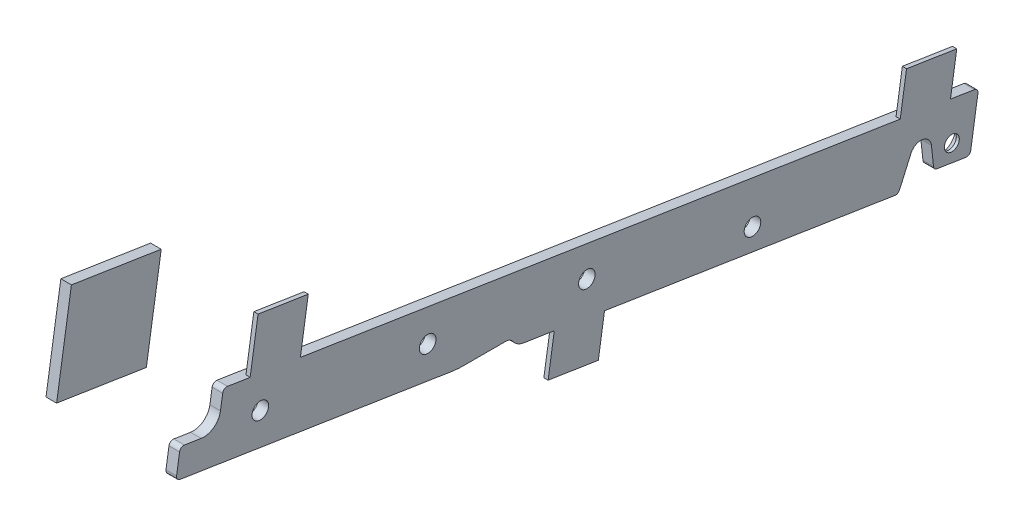
SolidWorks part; units mm, degrees
material "6061-T6 (SS)"
ref_plane "Front Plane" through (0, 0, 0) normal (0, 0, 1) x (1, 0, 0)
ref_plane "Top Plane" through (0, 0, 0) normal (0, 1, 0) x (1, 0, 0)
ref_plane "Right Plane" through (0, 0, 0) normal (1, 0, 0) x (0, 0, -1)
sketch "Sketch1" plane through (0, 0, 0) normal (1, 0, 0) x (0, 0, -1)
  line L0 (0, 0) -> (-69.3361, 0) construction
  line L1 (0, 0) -> (0, 19.05) construction
  line L2 (0, 19.05) -> (-75.5537, 19.05) construction
  line L3 (-60.6679, 12.573) -> (-60.6679, 19.05) construction
  line L4 (-60.6679, 12.573) -> (-61.6659, 6.1734) construction
  line L5 (-60.6679, 12.573) -> (-9.8679, 12.573) construction
  line L6 (-9.8679, 12.573) -> (-9.8679, 9.12) construction
  line L7 (-60.6679, 12.573) -> (-111.4679, 12.573) construction
  line L8 (-111.4679, 12.573) -> (-111.4679, 10.7443) construction
  line L9 (-60.6679, 12.573) -> (-110.8612, 20.4008) construction
  line L10 (-110.8612, 20.4008) -> (-110.3291, 23.8125) construction
  line L11 (-60.6679, 12.573) -> (-10.4746, 4.7452) construction
  line L12 (-10.4746, 4.7452) -> (-10.1928, 6.5521) construction
  line L13 (-233.578, 32.9834) -> (-149.1199, 19.812)
  line L14 (-13.1312, 7.852) -> (-16.9583, -0.7989)
  line L15 (-6.9981, 6.8955) -> (-6.2681, 0.1046)
  line L16 (-6.2681, 0.1046) -> (4.6041, -1.5909)
  line L17 (4.6041, -1.5909) -> (7.1482, 14.7219)
  line L18 (7.1482, 14.7219) -> (-219.3491, 50.0447)
  line L19 (-220.9929, 39.5041) -> (-219.3491, 50.0447)
  line L20 (-220.9929, 39.5041) -> (-232.2864, 41.2653)
  line L21 (-232.2864, 41.2653) -> (-233.578, 32.9834)
  line L22 (-206.8007, 48.0877) -> (-209.7361, 29.2652) construction
  line L23 (-208.2684, 38.6765) -> (-158.0751, 30.8487) construction
  line L24 (-134.62, 17.5507) -> (-134.62, 19.812) construction
  line L25 (-134.62, 19.812) -> (-149.1199, 19.812)
  line L26 (-132.0827, 17.155) -> (-16.9583, -0.7989)
  circle A0 centre (-9.8679, 9.12) radius 4.7879 construction
  circle A1 centre (-111.4679, 10.7443) radius 3.175 construction
  circle A2 centre (-60.6679, 12.573) radius 4.953 construction
  circle A3 centre (-110.3291, 23.8125) radius 2.4892
  circle A4 centre (-110.3291, 23.8125) radius 4.7625 construction
  arc A5 (-6.9981, 6.8955) -> (-13.1312, 7.852) centre (-10.1928, 6.5521) ccw
  circle A6 centre (-60.6679, 12.573) radius 2.4892
  circle A7 centre (-208.2684, 38.6765) radius 5.2942 construction
  circle A8 centre (-158.0751, 30.8487) radius 5.917 construction
  circle A9 centre (-208.2684, 38.6765) radius 2.4892
  circle A10 centre (-158.0751, 30.8487) radius 2.4892
  arc A11 (-134.62, 19.812) -> (-132.0827, 17.155) centre (-134.62, 17.272) cw
  dimension "D1" = 9.5758
  dimension "D2" = 5.08
  dimension "D5" = 6.35
  dimension "D6" = 101.6
  dimension "D8" = 9.906
  dimension "D9" = 1.524
  dimension "D12" = 4.9784
  dimension "D13" = 9.525
  dimension "D14" = 75
  dimension "D15" = 6.4262
  dimension "D20" = 11.43
  dimension "D22" = 12.7
  dimension "D26" = 2.54
  dimension "D3" = 9.12
  dimension "D4" = 19.05
  dimension "D7" = 10.7443
  dimension "D10" = 6.477
  dimension "D11" = 50.8
  dimension "D16" = 2.54
  dimension "D17" = 19.05
  dimension "D18" = 15.875
  dimension "D19" = 111.76
  dimension "D21" = 8.382
  dimension "D23" = 50.8
  dimension "D24" = 134.62
  dimension "D25" = 0.762
extrude "Boss-Extrude1" add sketch "Sketch1" along normal mid plane 3.175
fillet "Fillet1" radius 5.08 1 edges at (0, 39.5041, 220.9929)
fillet "Fillet2" radius 25.4 1 edges at (0, 19.812, 149.1199)
fillet "Fillet3" radius 5.08 1 edges at (0, 17.155, 132.0827)
fillet "Fillet4" radius 1.27 7 edges at (0, 41.2653, 232.2864) (0, 50.0447, 219.3491) (0, 14.7219, -7.1482) (0, -1.5909, -4.6041) (0, 0.1046, 6.2681) (0, -0.7989, 16.9583) (0, 32.9834, 233.578)
hole_wizard "CSK for #8 Oval Head Machine Screw1" positions "Sketch2" profile "Sketch3" countersink size "#8" standard "ANSI Inch" end condition through all
sketch "Sketch2" plane through (-1.5875, 0, 0) normal (-1, 0, 0) x (0, 0, 1)
  line L0 (0.8872, 4.4069) -> (-0.874, 15.7004) construction
  line L1 (-5.8933, 14.9176) -> (218.0942, 49.849) construction
  line L3 (-4.7998, -0.3361) -> (-6.9525, 13.4671) construction
  line L4 (5.3052, -0.0455) -> (-3.3493, -1.3952) construction
  point P0 (0.8872, 4.4069)
  dimension "D1" = 6.35
  dimension "D2" = 5.08
sketch "Sketch3" plane through (-1.5875, 4.4069, 0.8872) normal (0, 1, 0) x (0, 0, 1)
  line L0 (0, 0) -> (0, 3.175)
  line L1 (0, 3.175) -> (2.2479, 3.175)
  line L2 (2.2479, 3.175) -> (2.2479, 2.2645)
  line L3 (2.2479, 2.2645) -> (4.2164, 0)
  line L5 (4.2164, 0) -> (0, 0)
  line L6 (-2.2479, 2.2645) -> (-4.2164, 0) construction
  line L11 (0, -6.35) -> (0, 107.95) construction
  dimension "Thru Hole Dia." = 4.4958
  dimension "Thru Hole Depth" = 3.175
  dimension "Near C'Sink Dia." = 8.4328
  dimension "Near C'Sink Angle" = 82
sketch "Sketch4" plane through (-1.5875, 0, 0) normal (-1, 0, 0) x (0, 0, 1)
  line L35 (24.2002, 1.6659) -> (15.6235, 21.0533)
  line L36 (16.564, 0.0923) -> (13.1312, 7.852) construction
  line L43 (-1.3461, 10.4854) -> (0.2195, 0.4467)
  line L44 (215.1125, 44.2426) -> (-1.3461, 10.4854)
  line L45 (215.1908, 43.7406) -> (215.1125, 44.2426)
  line L46 (150.2823, 25.1347) -> (220.8478, 36.1395)
  line L47 (134.62, 24.892) -> (147.1512, 24.892)
  line L48 (17.1384, 4.3706) -> (128.4388, 21.7281)
  line L49 (-1.3461, 10.4854) -> (0.2195, 0.4467)
  line L50 (215.1125, 44.2426) -> (-1.3461, 10.4854)
  line L51 (215.1908, 43.7406) -> (215.1125, 44.2426)
  line L52 (150.2823, 25.1347) -> (220.8478, 36.1395)
  line L53 (134.62, 24.892) -> (147.1512, 24.892)
  line L54 (17.1384, 4.3706) -> (128.4388, 21.7281)
  circle A39 centre (60.6679, 12.573) radius 7.5692
  circle A40 centre (110.3291, 23.8125) radius 7.5692
  circle A41 centre (158.0751, 30.8487) radius 7.5692
  circle A42 centre (208.2684, 38.6765) radius 7.5692
  circle A43 centre (60.6679, 12.573) radius 2.4892 construction
  arc A48 (215.1908, 43.7406) -> (220.8478, 36.1395) centre (225.2294, 45.3062) ccw
  arc A49 (147.1512, 24.892) -> (150.2823, 25.1347) centre (147.1512, 45.212) ccw
  arc A50 (134.62, 24.892) -> (128.4388, 21.7281) centre (134.62, 17.272) ccw
  arc A51 (215.1908, 43.7406) -> (220.8478, 36.1395) centre (225.2294, 45.3062) ccw
  arc A52 (147.1512, 24.892) -> (150.2823, 25.1347) centre (147.1512, 45.212) ccw
  arc A53 (134.62, 24.892) -> (128.4388, 21.7281) centre (134.62, 17.272) ccw
  dimension "D2" = 5.08
  dimension "D3" = 7.62
  dimension "D1" = 5.08
extrude "Cut-Extrude1" [suppressed] cut sketch "Sketch4" against normal through all contours A39 L50 L35 L54 | A40 L50 A39 L54 | A53 L53 A52 L52 A41 L50 A40 L54 | A42 L50 A41 L52
fillet "Fillet5" [suppressed] radius 3.302
sketch "Sketch5" plane through (1.5875, 0, 0) normal (1, 0, 0) x (0, 0, -1)
  line L0 (-211.3094, 48.7909) -> (-196.2515, 46.4425)
  line L1 (-211.3094, 48.7909) -> (-208.933, 64.0294)
  line L2 (-196.2515, 46.4425) -> (-193.875, 61.6811)
  line L3 (-208.933, 64.0294) -> (-193.875, 61.6811)
  line L4 (5.8933, 14.9176) -> (-218.0942, 49.849) construction
  line L5 (-16.3482, 18.3862) -> (-1.2902, 16.0379)
  line L6 (-16.3482, 18.3862) -> (-14.4568, 30.5144)
  line L7 (-1.2902, 16.0379) -> (0.6012, 28.1661)
  line L8 (-14.4568, 30.5144) -> (0.6012, 28.1661)
  line L9 (-120.0994, 15.2862) -> (-105.0414, 12.9379)
  line L10 (-120.0994, 15.2862) -> (-121.9593, 3.3601)
  line L11 (-105.0414, 12.9379) -> (-106.9013, 1.0118)
  line L12 (-121.9593, 3.3601) -> (-106.9013, 1.0118)
  line L13 (-129.2216, 16.7088) -> (-17.9212, -0.6487) construction
  dimension "D1" = 15.24
extrude "Boss-Extrude2" add sketch "Sketch5" against normal blind 1.27
sketch "Sketch6" plane through (1.5875, 0, 0) normal (1, 0, 0) x (0, 0, -1)
  line L0 (-237.9835, 95.4074) -> (-242.4269, 66.915)
  line L1 (-237.9835, 95.4074) -> (-264.9166, 99.6076)
  line L2 (-242.4269, 66.915) -> (-269.36, 71.1152)
  line L3 (-264.9166, 99.6076) -> (-269.36, 71.1152)
  line L4 (-232.3231, 32.7877) -> (-151.0651, 20.1154) construction
extrude "Boss-Extrude3" add sketch "Sketch6" against normal up to surface (3.175 mm away) separate body up to face at (-1.5875, 4.4069, 5.1036)
